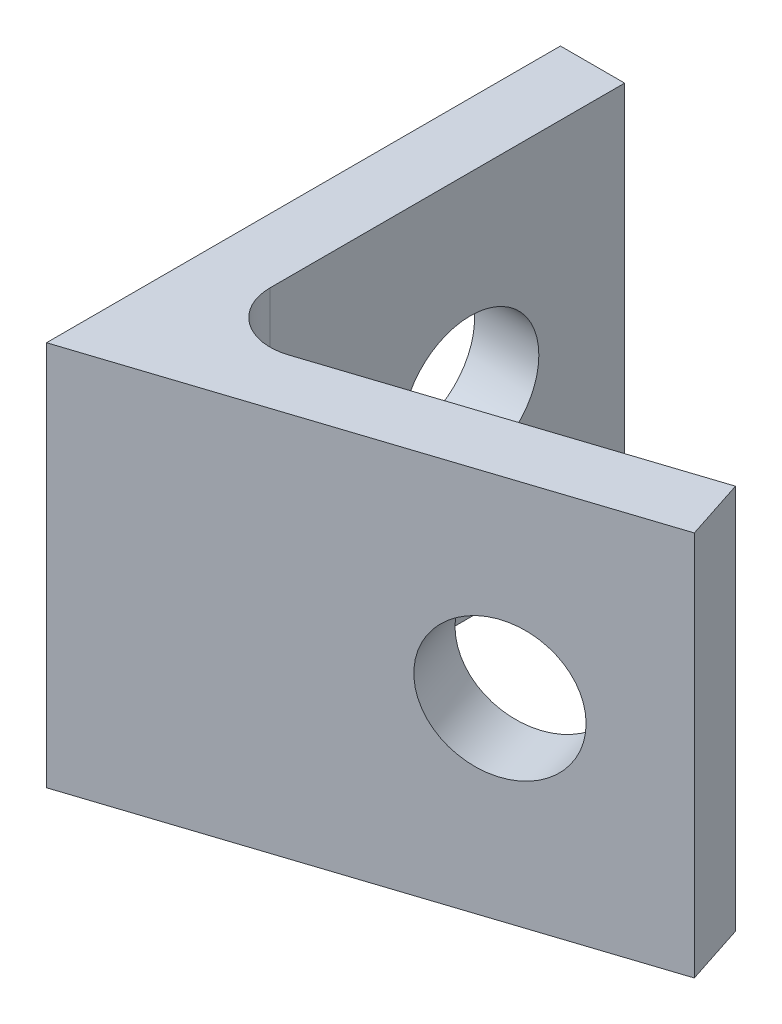
SolidWorks part; units mm, degrees
material "ABS"
ref_plane "Front" through (0, 0, 0) normal (0, 0, 1) x (1, 0, 0)
ref_plane "Top" through (0, 0, 0) normal (0, 1, 0) x (1, 0, 0)
ref_plane "Right" through (0, 0, 0) normal (1, 0, 0) x (0, 0, -1)
sketch "Sketch1" plane through (0, 0, 0) normal (0, 1, 0) x (1, 0, 0)
  line L0 (0, 0) -> (0, 25.4)
  line L1 (0, -50) -> (0, 50) construction
  line L2 (0, 25.4) -> (3.175, 25.4)
  line L3 (3.175, 25.4) -> (3.175, 4.3733)
  line L4 (3.175, 4.3733) -> (23.1678, 10.8854)
  line L5 (23.1678, 10.8854) -> (24.1511, 7.8665)
  line L6 (24.1511, 7.8665) -> (0, 0)
  line L7 (3.175, 4.3733) -> (3.175, 80.5733) construction
  line L8 (3.175, 80.5733) -> (86.375, 53.4733) construction
  line L9 (86.375, 53.4733) -> (86.375, 31.4733) construction
  line L10 (86.375, 31.4733) -> (3.175, 4.3733) construction
  dimension "D1" = 25.4
  dimension "D2" = 3.175
  dimension "D3" = 76.2
  dimension "D4" = 83.2
  dimension "D5" = 22
extrude "Boss-Extrude1" add sketch "Sketch1" along normal blind 19.05 contours L4 L5 L6 L0 L2 L3
fillet "Fillet1" radius 2.54 1 edges at (3.175, 9.525, -4.3733)
hole_wizard "1/4 Clearance Hole1" positions "Sketch3" profile "Sketch4" hole size "1/4" standard "ANSI Inch" end condition up to next
sketch "Sketch3" plane through (0, 0, 0) normal (-1, 0, 0) x (0, 0, 1)
  line L0 (-17.78, 19.05) -> (-17.78, 0) construction
  line L1 (0, 19.05) -> (-25.4, 19.05) construction
  line L2 (50, 0) -> (-50, 0) construction
  line L4 (0, -50) -> (0, 50) construction
  point P0 (-17.78, 9.525)
  dimension "D1" = 17.78
sketch "Sketch4" plane through (0, 9.525, -17.78) normal (0, 1, 0) x (0, 0, 1)
  line L0 (0, 0) -> (0, 3.175)
  line L1 (0, 3.175) -> (3.3782, 3.175)
  line L2 (3.3782, 3.175) -> (3.3782, 0)
  line L5 (3.3782, 0) -> (0, 0)
  line L11 (0, -6.35) -> (0, 107.95) construction
  dimension "Thru Hole Dia." = 6.7564
  dimension "Thru Hole Depth" = 3.175
hole_wizard "1/4 Clearance Hole2" positions "Sketch5" profile "Sketch6" hole size "1/4" standard "ANSI Inch" end condition up to next
sketch "Sketch5" plane through (0, 0, 0) normal (0.3097, 0, 0.9508) x (0.9508, 0, -0.3097)
  line L0 (17.78, 19.05) -> (17.78, 0) construction
  line L1 (25.4, 19.05) -> (0, 19.05) construction
  line L2 (50, 0) -> (-50, 0) construction
  line L4 (0, 19.05) -> (0, 0) construction
  point P0 (17.78, 9.525)
  dimension "D1" = 17.78
sketch "Sketch6" plane through (16.9058, 9.525, -5.5066) normal (0, 1, 0) x (0.9508, 0, -0.3097)
  line L0 (0, 0) -> (0, 3.175)
  line L1 (0, 3.175) -> (3.3782, 3.175)
  line L2 (3.3782, 3.175) -> (3.3782, 0)
  line L5 (3.3782, 0) -> (0, 0)
  line L11 (0, -6.35) -> (0, 107.95) construction
  dimension "Thru Hole Dia." = 6.7564
  dimension "Thru Hole Depth" = 3.175
